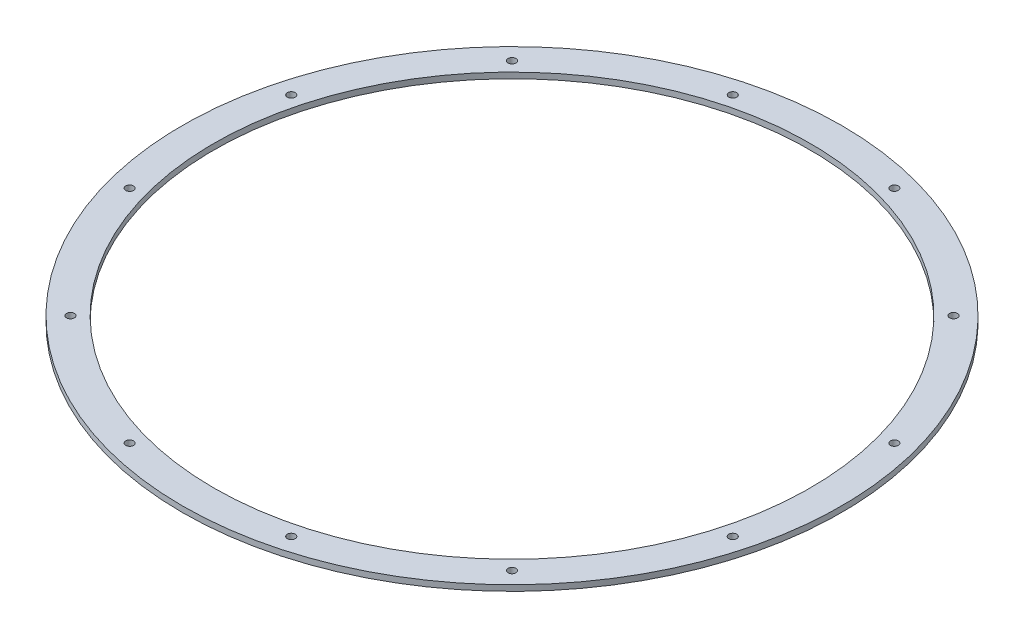
SolidWorks part; units mm, degrees
material "AISI 304"
ref_plane "Piano frontale" through (0, 0, 0) normal (0, 0, 1) x (1, 0, 0)
ref_plane "Piano superiore" through (0, 0, 0) normal (0, 1, 0) x (1, 0, 0)
ref_plane "Piano destro" through (0, 0, 0) normal (1, 0, 0) x (0, 0, -1)
sketch "Schizzo1" plane through (0, 0, 0) normal (0, 1, 0) x (1, 0, 0)
  line L0 (300, 0) -> (-300, 0) construction
  line L1 (0, -300) -> (0, 300) construction
  circle A0 centre (0, 0) radius 258
  arc A1 (-285, 0) -> (285, 0) centre (0, 0) ccw
  circle A2 centre (0, 0) radius 270 construction
  circle A3 centre (-260.8, 69.8811) radius 3.4
  circle A4 centre (-190.9188, 190.9188) radius 3.4
  circle A5 centre (-69.8811, 260.8) radius 3.4
  circle A6 centre (69.8811, 260.8) radius 3.4
  circle A7 centre (190.9188, 190.9188) radius 3.4
  circle A8 centre (260.8, 69.8811) radius 3.4
  circle A9 centre (260.8, -69.8811) radius 3.4
  circle A10 centre (190.9188, -190.9188) radius 3.4
  circle A11 centre (69.8811, -260.8) radius 3.4
  circle A12 centre (-69.8811, -260.8) radius 3.4
  circle A13 centre (-190.9188, -190.9188) radius 3.4
  circle A14 centre (-260.8, -69.8811) radius 3.4
  arc A15 (285, 0) -> (-285, 0) centre (0, 0) ccw
  point P7 (0, 0)
  point P11 (-385, -300)
  point P34 (0, 0)
  point P36 (0, 0)
  point P37 (-385, 300)
  dimension "D1" = 12
extrude "Estrusione-Estrusione1" add sketch "Schizzo1" along normal mid plane 5
ref_plane "Piano1" through (0, 2.5, 0) normal (0, 1, 0) x (1, 0, 0)
